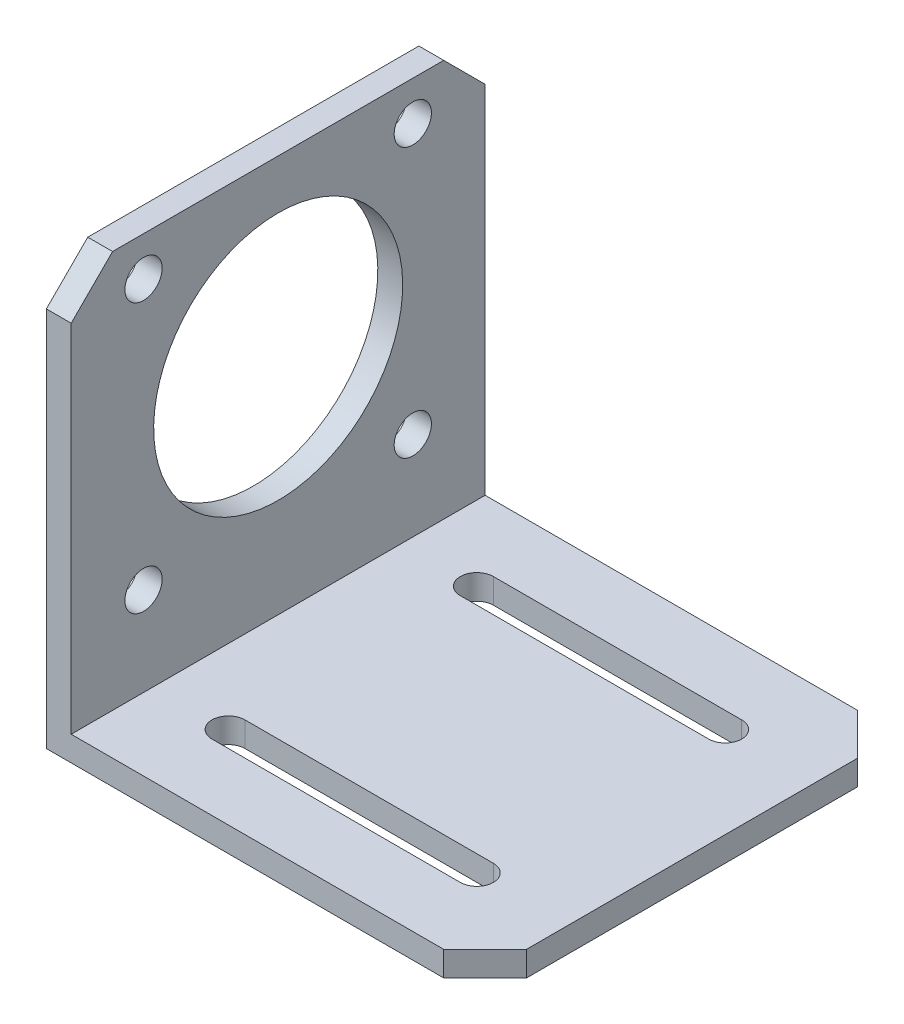
SolidWorks part; units mm, degrees
ref_plane "前视基准面" through (0, 0, 0) normal (0, 0, 1) x (1, 0, 0)
ref_plane "上视基准面" through (0, 0, 0) normal (0, 1, 0) x (1, 0, 0)
ref_plane "右视基准面" through (0, 0, 0) normal (1, 0, 0) x (0, 0, -1)
other "Configuration Table"
sketch "草图1" plane through (0, 0, 0) normal (0, 0, 1) x (1, 0, 0)
  line L0 (0, 0) -> (53, 0)
  line L1 (53, 0) -> (53, 3)
  line L2 (53, 3) -> (3, 3)
  line L3 (3, 3) -> (3, 51)
  line L4 (3, 51) -> (0, 51)
  line L5 (0, 51) -> (0, 0)
  dimension "D1" = 51
  dimension "D2" = 53
  dimension "D3" = 3
  dimension "D4" = 3
extrude "凸台-拉伸1" add sketch "草图1" along normal blind 50
chamfer "倒角1" distance 5 angle 45 4 edges at (53, 1.5, 50) (53, 1.5, 0) (1.5, 51, 0) (1.5, 51, 50)
sketch "草图2" plane through (3, 0, 0) normal (1, 0, 0) x (0, 0, -1)
  line L0 (-45, 51) -> (-5, 51) construction
  line L1 (-50, 3) -> (-50, 46) construction
  line L2 (-1025, 30) -> (48975, 30) construction
  line L3 (-25, -970) -> (-25, 49030) construction
  circle A0 centre (-25, 30) radius 15.04
  circle A1 centre (-8.735, 46.265) radius 2.25
  circle A2 centre (-41.265, 46.265) radius 2.25
  circle A3 centre (-8.735, 13.735) radius 2.25
  circle A4 centre (-41.265, 13.735) radius 2.25
  dimension "D1" = 21
  dimension "D2" = 30.08
  dimension "D4" = 4.5
  dimension "D3" = 25
  dimension "D5" = 16.265
  dimension "D6" = 16.265
extrude "切除-拉伸1" cut sketch "草图2" against normal through all both and the other way through all
sketch "草图4" plane through (0, 3, 0) normal (0, 1, 0) x (1, 0, 0)
  line L0 (-947, -25) -> (49053, -25) construction
  line L1 (53, -45) -> (53, -5) construction
  line L2 (12, -12) -> (42, -12)
  line L3 (12, -8) -> (42, -8)
  line L4 (12, -38) -> (42, -38)
  line L5 (12, -42) -> (42, -42)
  arc A0 (42, -12) -> (42, -8) centre (42, -10) ccw
  arc A1 (12, -8) -> (12, -12) centre (12, -10) ccw
  arc A2 (12, -42) -> (12, -38) centre (12, -40) cw
  arc A3 (42, -38) -> (42, -42) centre (42, -40) cw
  point P5 (53, -25)
  dimension "D1" = 15
  dimension "D6" = 4
  dimension "D3" = 11
  dimension "D4" = 15
  dimension "D5" = 30
extrude "切除-拉伸2" cut sketch "草图4" against normal through all both
